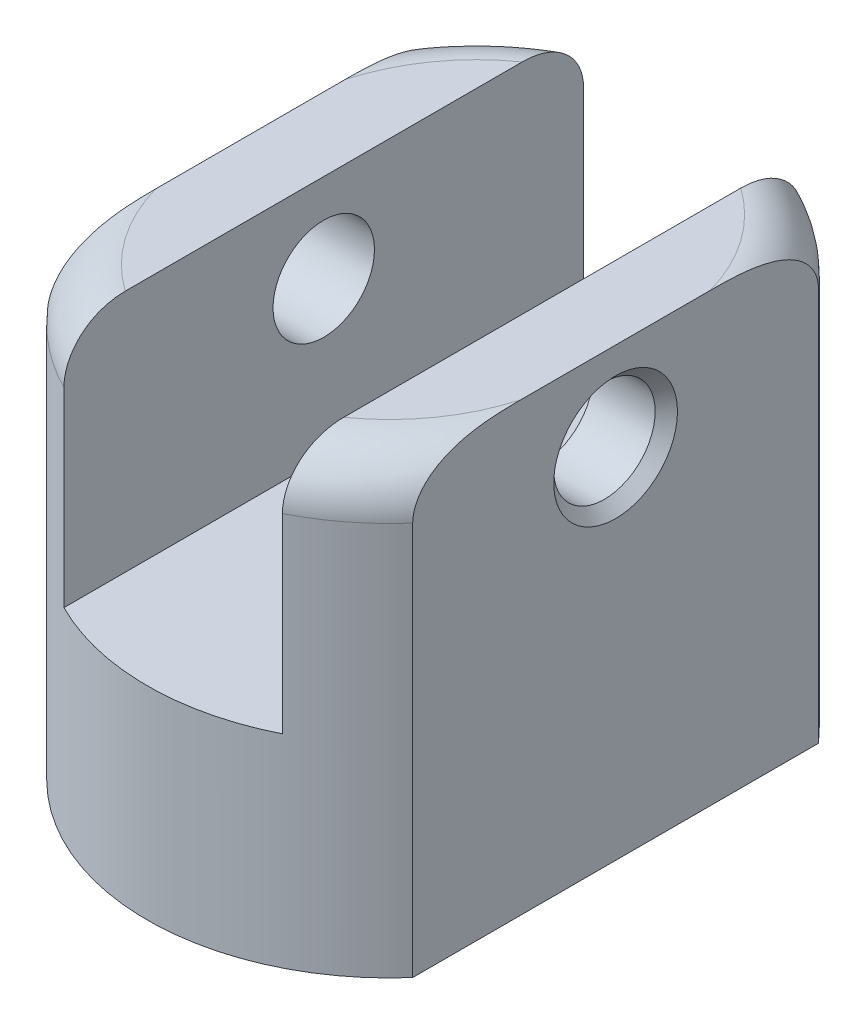
SolidWorks part; units mm, degrees
ref_plane "Front Plane" through (0, 0, 0) normal (0, 0, 1) x (1, 0, 0)
ref_plane "Top Plane" through (0, 0, 0) normal (0, 1, 0) x (1, 0, 0)
ref_plane "Right Plane" through (0, 0, 0) normal (1, 0, 0) x (0, 0, -1)
sketch "Sketch1" plane through (0, 0, 0) normal (0, 1, 0) x (1, 0, 0)
  line L0 (-4.5, 0) -> (-4.5, 10)
  line L1 (0, -55) -> (0, 55) construction
  line L2 (4.5, 0) -> (4.5, 10)
  arc A0 (-4.5, 10) -> (4.5, 10) centre (0, 6.0699) cw
  arc A1 (-4.5, 0) -> (4.5, 0) centre (0, 3.9301) ccw
  dimension "D1" = 10
  dimension "D2" = 4.5
extrude "Boss-Extrude1" add sketch "Sketch1" along normal blind 5
sketch "Sketch2" plane through (0, 5, 0) normal (0, 1, 0) x (1, 0, 0)
  line L0 (-2.6926, 11.4034) -> (-2.6926, -1.4034)
  line L1 (-4.5, 10) -> (-4.5, 0)
  line L2 (-4.5, 10) -> (-4.5, 0) construction
  line L3 (0, -55) -> (0, 55) construction
  line L4 (4.5, 10) -> (4.5, 0)
  line L5 (2.6926, 11.4034) -> (2.6926, -1.4034)
  arc A0 (4.5, 10) -> (-4.5, 10) centre (0, 6.0699) ccw construction
  arc A1 (-4.5, 0) -> (4.5, 0) centre (0, 3.9301) ccw construction
  arc A2 (-2.6926, 11.4034) -> (-4.5, 10) centre (0, 6.0699) ccw
  arc A3 (-4.5, 0) -> (-2.6926, -1.4034) centre (0, 3.9301) ccw
  arc A4 (2.6926, 11.4034) -> (4.5, 10) centre (0, 6.0699) cw
  arc A5 (4.5, 0) -> (2.6926, -1.4034) centre (0, 3.9301) cw
extrude "Boss-Extrude2" add sketch "Sketch2" along normal blind 6
fillet "Fillet1" radius 1.3 4 edges at (3.6641, 11, -10.789) (3.6641, 11, 0.789) (-3.6641, 11, -10.789) (-3.6641, 11, 0.789)
hole_wizard "M3 Tapped Hole1" positions "Sketch3" profile "Sketch5" tap size "M3" standard "ISO" end condition through all
sketch "Sketch3" plane through (4.5, 0, 0) normal (1, 0, 0) x (0, 0, -1)
  point P0 (5, 8.8188)
sketch "Sketch5" plane through (4.5, 8.8188, -5) normal (0, 1, 0) x (0, 0, -1)
  line L0 (0, 0) -> (0, 9)
  line L1 (0, 9) -> (1.25, 9)
  line L2 (1.25, 9) -> (1.25, 0.275)
  line L3 (1.25, 0.275) -> (1.525, 0)
  line L5 (1.525, 0) -> (0, 0)
  line L6 (-1.25, 0.275) -> (-1.525, 0) construction
  line L11 (0, -6.35) -> (0, 107.95) construction
  dimension "Thru Tap Drill Dia." = 2.5
  dimension "Thru Tap Drill Depth" = 9
  dimension "Near C'Sink Dia." = 3.05
  dimension "Near C'Sink Angle" = 90
cosmetic thread "Hole Thread1" parameters "D2"=3
